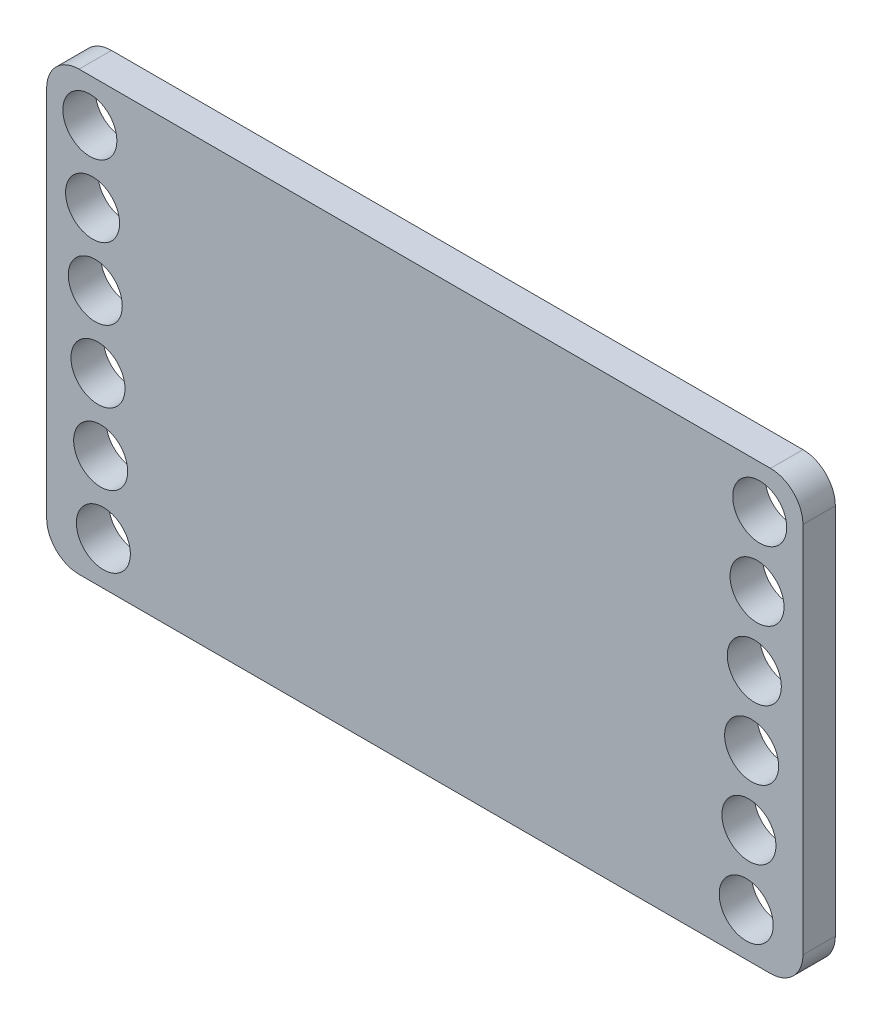
SolidWorks part; units mm, degrees
ref_plane "Front Plane" through (0, 0, 0) normal (0, 0, 1) x (1, 0, 0)
ref_plane "Top Plane" through (0, 0, 0) normal (0, 1, 0) x (1, 0, 0)
ref_plane "Right Plane" through (0, 0, 0) normal (1, 0, 0) x (0, 0, -1)
sketch "Sketch1" plane through (0, 0, 0) normal (0, 0, 1) x (1, 0, 0)
  line L0 (0, 0) -> (0, 40.9962) construction
  line L1 (-35, -40) -> (35, -40)
  line L2 (-35, -40) -> (-35, 40)
  line L3 (-35, 40) -> (35, 40)
  line L4 (35, -40) -> (35, 40)
  line L5 (-35, -40) -> (35, 40) construction
  line L6 (-35, 40) -> (35, -40) construction
  line L7 (35, 23) -> (-35, 23) construction
  line L8 (-35, 16.5) -> (35, 16.5) construction
  line L9 (35, 10) -> (-35, 10) construction
  line L10 (-35, -0.5) -> (35, -0.5)
  line L11 (-35, 29.5) -> (35, 29.5) construction
  line L12 (35, 36) -> (-35, 36) construction
  line L13 (-35, 3.5) -> (35, 3.5) construction
  circle A0 centre (30.5, 23) radius 2.5
  circle A1 centre (-30.5, 23) radius 2.5
  circle A2 centre (-30.25, 16.5) radius 2.5
  circle A3 centre (30.25, 16.5) radius 2.5
  circle A4 centre (30, 10) radius 2.5
  circle A5 centre (-30, 10) radius 2.5
  circle A6 centre (-31, 36) radius 2.5
  circle A7 centre (-30.75, 29.5) radius 2.5
  circle A8 centre (30.75, 29.5) radius 2.5
  circle A9 centre (31, 36) radius 2.5
  circle A10 centre (-29.75, 3.5) radius 2.5
  circle A11 centre (29.75, 3.5) radius 2.5
  point P0 (0, 0)
  dimension "D9" = 5
  dimension "D14" = 5
  dimension "D15" = 5
  dimension "D3" = 1.5
  dimension "D1" = 80
  dimension "D2" = 70
  dimension "D4" = 6.5
  dimension "D5" = 6.5
  dimension "D6" = 60
  dimension "D7" = 61
  dimension "D8" = 60.5
  dimension "D10" = 62
  dimension "D11" = 6.5
  dimension "D12" = 6.5
  dimension "D13" = 61.5
  dimension "D16" = 59.5
  dimension "D17" = 6.5
  dimension "D18" = 1.5
extrude "Boss-Extrude1" add sketch "Sketch1" along normal blind 3 contours L2 L10 L4 L3 A11 A10 A9 A8 A7 A6 A5 A4 A3 A2 A1 A0
fillet "Fillet1" radius 3 4 edges at (35, 40, 1.5) (-35, 40, 1.5) (35, -0.5, 1.5) (-35, -0.5, 1.5)
